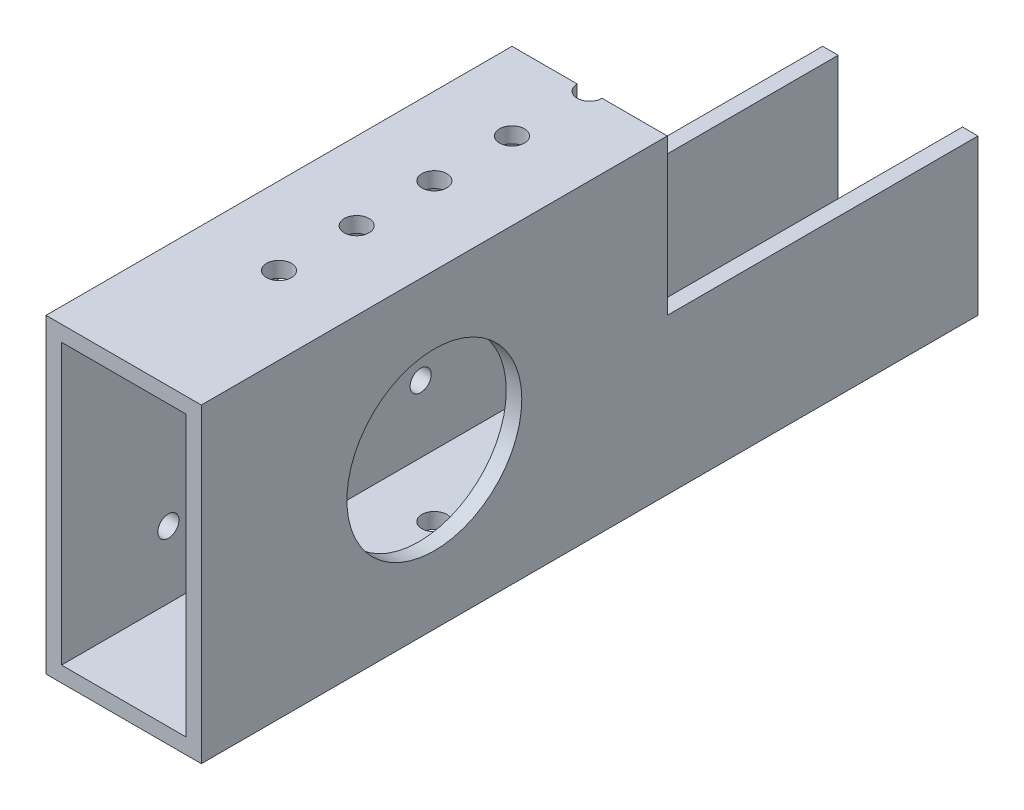
SolidWorks part; units mm, degrees
ref_plane "Front Plane" through (0, 0, 0) normal (0, 0, 1) x (1, 0, 0)
ref_plane "Top Plane" through (0, 0, 0) normal (0, 1, 0) x (1, 0, 0)
ref_plane "Right Plane" through (0, 0, 0) normal (1, 0, 0) x (0, 0, -1)
sketch "Sketch1" plane through (0, 0, 0) normal (0, 0, 1) x (1, 0, 0)
  line L0 (-10.16, -22.86) -> (-10.16, 22.86)
  line L1 (-12.7, -25.4) -> (12.7, -25.4)
  line L2 (-12.7, -25.4) -> (-12.7, 25.4)
  line L3 (-12.7, 25.4) -> (12.7, 25.4)
  line L4 (12.7, -25.4) -> (12.7, 25.4)
  line L5 (-12.7, -25.4) -> (12.7, 25.4) construction
  line L6 (-12.7, 25.4) -> (12.7, -25.4) construction
  line L7 (-10.16, 22.86) -> (10.16, 22.86)
  line L8 (10.16, -22.86) -> (10.16, 22.86)
  line L9 (-10.16, -22.86) -> (10.16, -22.86)
  point P0 (0, 0)
  dimension "D1" = 25.4
  dimension "D2" = 50.8
  dimension "D3" = 2.54
extrude "Boss-Extrude1" add sketch "Sketch1" along normal blind 127
sketch "Sketch2" plane through (0, 25.4, 0) normal (0, 1, 0) x (1, 0, 0)
  line L0 (12.7, 0) -> (-12.7, 0) construction
  circle A0 centre (0, -12.7) radius 2.032
  circle A1 centre (0, -25.4) radius 2.032
  circle A2 centre (0, -38.1) radius 2.032
  circle A3 centre (0, -50.8) radius 2.032
  circle A4 centre (0, -63.5) radius 2.032
  circle A5 centre (0, -76.2) radius 2.032
  circle A6 centre (0, -88.9) radius 2.032
  circle A7 centre (0, -101.6) radius 2.032
  dimension "D1" = 4.064
  dimension "D2" = 12.7
  dimension "D3" = 8
extrude "Cut-Extrude1" cut sketch "Sketch2" against normal through all
sketch "Sketch3" plane through (12.7, 0, 0) normal (1, 0, 0) x (0, 0, -1)
  line L0 (-127, -25.4) -> (-127, 25.4) construction
  circle A0 centre (-88.9, 0) radius 14.3002
  dimension "D1" = 28.6004
  dimension "D2" = 38.1
extrude "Cut-Extrude2" cut sketch "Sketch3" against normal through all
sketch "Sketch4" plane through (-12.7, 0, 0) normal (-1, 0, 0) x (0, 0, 1)
  line L1 (0, 25.4) -> (50.8, 25.4)
  line L2 (0, 25.4) -> (0, 0)
  line L3 (0, 0) -> (50.8, 0)
  line L4 (50.8, 25.4) -> (50.8, 0)
  dimension "D1" = 25.4
  dimension "D2" = 50.8
extrude "Cut-Extrude3" cut sketch "Sketch4" against normal up to next
hole_wizard "#8-32 Tapped Hole1" positions "Sketch5" profile "Sketch6" tap size "#8-32" standard "ANSI Inch"
sketch "Sketch5" plane through (-12.7, 0, 0) normal (-1, 0, 0) x (0, 0, 1)
  point P0 (109.5222, 11.9062)
  point P3 (109.5222, -11.9063)
  point P6 (68.2778, -11.9063)
  point P9 (68.2778, 11.9062)
sketch "Sketch6" plane through (-12.7, 11.9062, 109.5222) normal (0, 1, 0) x (0, 0, 1)
  line L0 (0, 0) -> (0, 2.54)
  line L1 (0, 2.54) -> (1.7272, 2.54)
  line L2 (1.7272, 2.54) -> (1.7272, 0)
  line L5 (1.7272, 0) -> (0, 0)
  line L11 (0, -6.35) -> (0, 107.95) construction
  dimension "Thru Tap Drill Dia." = 3.4544
  dimension "Thru Tap Drill Depth" = 2.54
cosmetic thread "Hole Thread1" parameters "D2"=4.1656
cosmetic thread "Hole Thread2" parameters "D2"=4.1656
cosmetic thread "Hole Thread3" parameters "D2"=4.1656
cosmetic thread "Hole Thread4" parameters "D2"=4.1656
